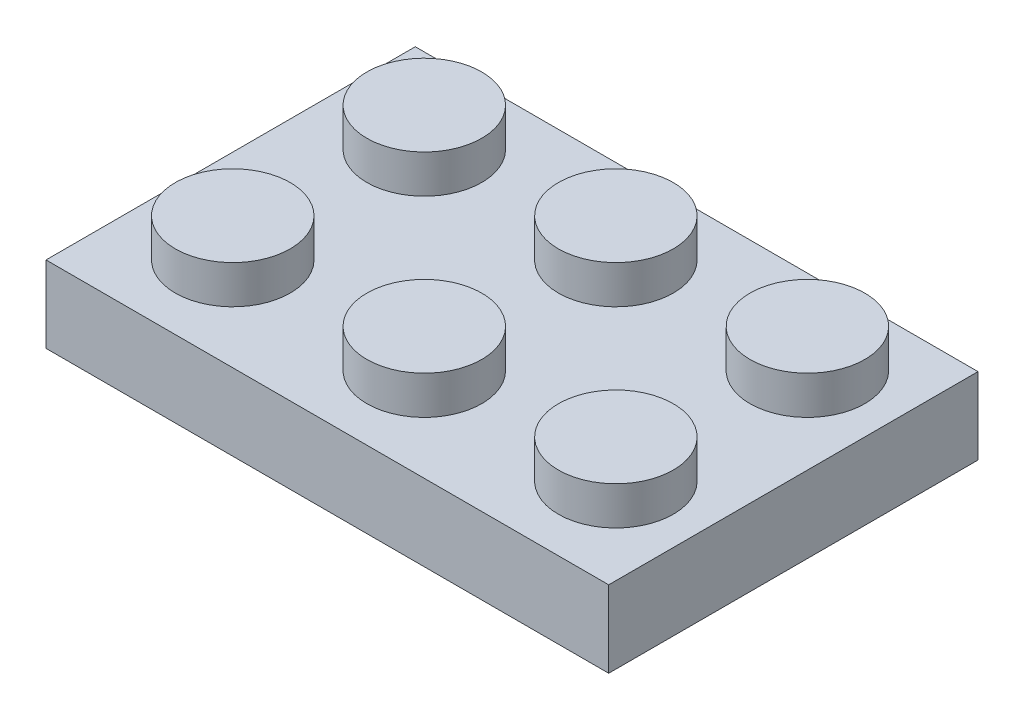
SolidWorks part; units mm, degrees
material "ABS"
ref_plane "Front Plane" through (0, 0, 0) normal (0, 0, 1) x (1, 0, 0)
ref_plane "Top Plane" through (0, 0, 0) normal (0, 1, 0) x (1, 0, 0)
ref_plane "Right Plane" through (0, 0, 0) normal (1, 0, 0) x (0, 0, -1)
sketch "Sketch1" plane through (0, 0, 0) normal (0, 0, 1) x (1, 0, 0)
  line L1 (0, 0) -> (23.5017, 0)
  line L2 (0, 0) -> (0, 3.2)
  line L3 (0, 3.2) -> (23.5017, 3.2)
  line L4 (23.5017, 0) -> (23.5017, 3.2)
  line L5 (0, 0) -> (23.5017, 3.2) construction
  line L6 (0, 3.2) -> (23.5017, 0) construction
  point P4 (11.7508, 1.6)
  dimension "D1" = 23.5017
  dimension "D2" = 3.2
extrude "Boss-Extrude1" add sketch "Sketch1" against normal blind 15.4232
sketch "Sketch2" plane through (0, 3.2, 0) normal (0, 1, 0) x (1, 0, 0)
  line L0 (23.5017, 0) -> (0, 0) construction
  circle A0 centre (3.9, 3.9) radius 2.4
  dimension "D1" = 4.8
  dimension "D2" = 3.9
  dimension "D3" = 3.9
extrude "Boss-Extrude2" add sketch "Sketch2" along normal blind 1.6
pattern_linear "LPattern1" count 2 spacing 8 along (0, 0, -1) count 4 spacing 8 along (1, 0, 0) of "Boss-Extrude2"
shell "Shell1" thickness 1.2
sketch "Sketch4" plane through (0, 2, 0) normal (0, -1, 0) x (1, 0, 0)
  line L0 (0, -15.4232) -> (0, 0) construction
  line L1 (0, 0) -> (23.5017, 0) construction
  circle A0 centre (7.9, -7.9) radius 3.25
  circle A1 centre (7.9, -7.9) radius 2.4
  dimension "D1" = 4.8
  dimension "D2" = 6.5
  dimension "D3" = 7.9
  dimension "D4" = 7.9
extrude "Boss-Extrude3" add sketch "Sketch4" along normal offset from surface (1.8 mm away) 0.2 up to face at (11.7508, 0, -7.7116)
pattern_linear "LPattern2" count 2 spacing 8 along (1, 0, 0) of "Boss-Extrude3"
